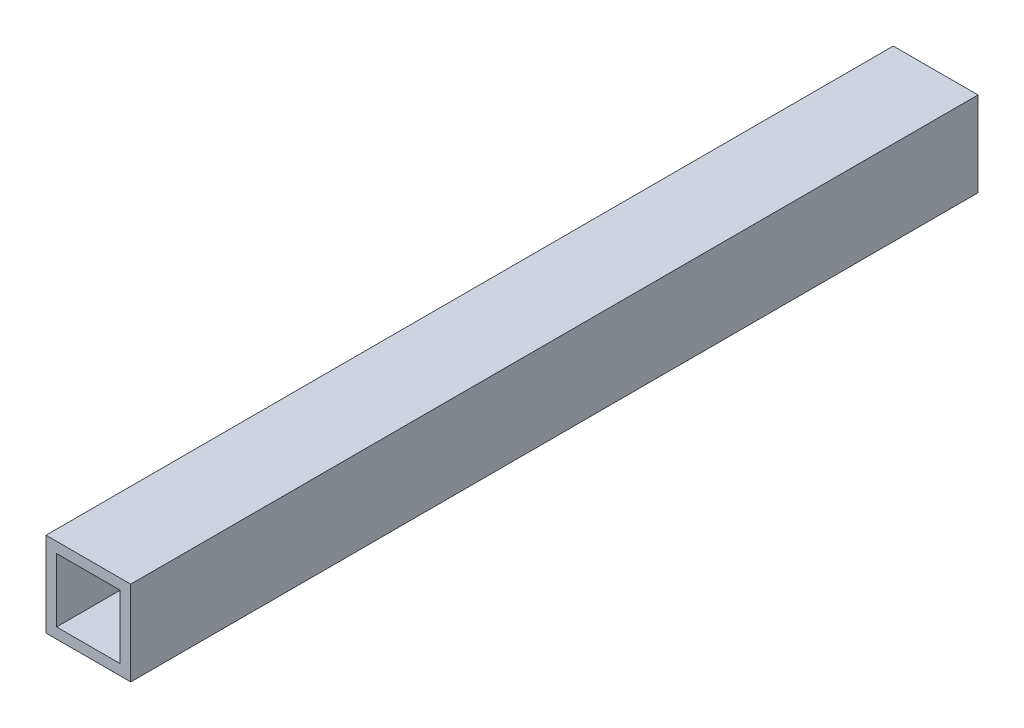
SolidWorks part; units mm, degrees
material "Д16Т ГОСТ 4784-74"
ref_plane "Спереди" through (0, 0, 0) normal (0, 0, 1) x (1, 0, 0)
ref_plane "Сверху" through (0, 0, 0) normal (0, 1, 0) x (1, 0, 0)
ref_plane "Справа" through (0, 0, 0) normal (1, 0, 0) x (0, 0, -1)
sketch "Эскиз1" plane through (0, 0, 0) normal (0, 0, 1) x (1, 0, 0)
  line L1 (0, 0) -> (40, 0)
  line L2 (0, 0) -> (0, 40)
  line L3 (0, 40) -> (40, 40)
  line L4 (40, 0) -> (40, 40)
  dimension "D1" = 40
  dimension "D2" = 40
extrude "Вытянуть-Тонкостенный1" add sketch "Эскиз1" along normal blind 400 thin thin type one direction reverse wall 5
